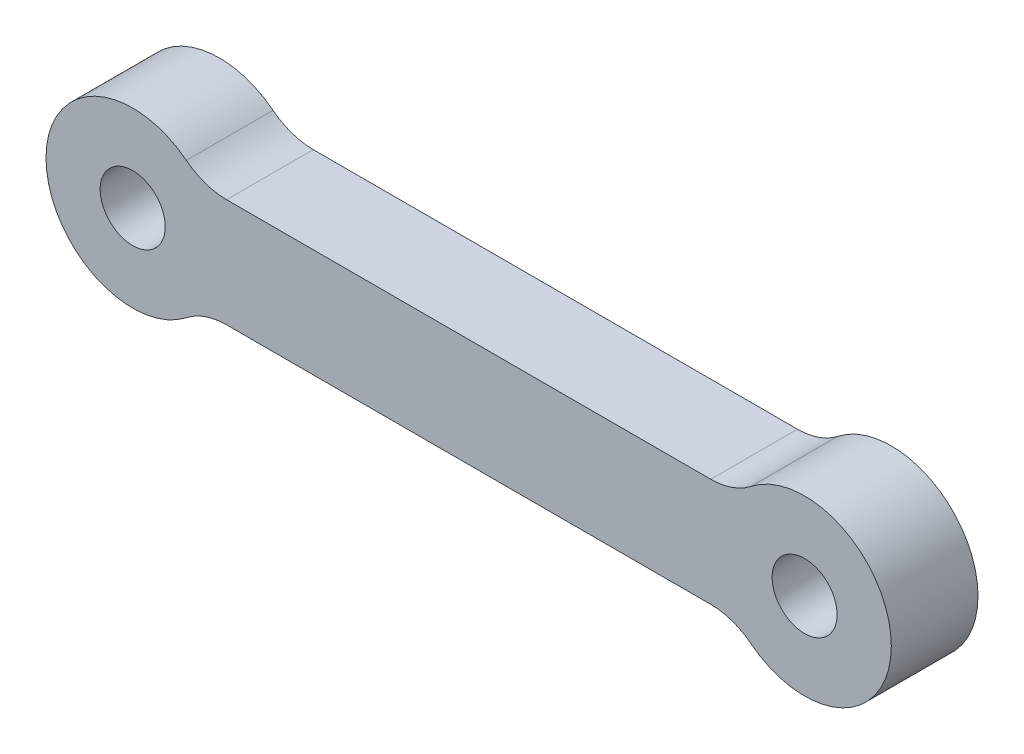
SolidWorks part; units mm, degrees
ref_plane "Front Plane" through (0, 0, 0) normal (0, 0, 1) x (1, 0, 0)
ref_plane "Top Plane" through (0, 0, 0) normal (0, 1, 0) x (1, 0, 0)
ref_plane "Right Plane" through (0, 0, 0) normal (1, 0, 0) x (0, 0, -1)
sketch "Sketch1" plane through (0, 0, 0) normal (0, 0, 1) x (1, 0, 0)
  line L0 (-15.5, 0) -> (15.5, 0) construction
  line L1 (0, 0) -> (0, 2.8532) construction
  line L3 (-11.1699, -2.5) -> (11.1699, -2.5)
  line L5 (-11.1699, 2.5) -> (11.1699, 2.5)
  line L7 (-12.3775, -2.5) -> (12.3775, 2.5) construction
  line L8 (-12.3775, 2.5) -> (12.3775, -2.5) construction
  circle A0 centre (-15.5, 0) radius 1.5
  arc A1 (-13.0256, 3.1429) -> (-13.0256, -3.1429) centre (-15.5, 0) ccw
  arc A2 (13.0256, 3.1429) -> (13.0256, -3.1429) centre (15.5, 0) cw
  circle A3 centre (15.5, 0) radius 1.5
  arc A4 (11.1699, 2.5) -> (13.0256, 3.1429) centre (11.1699, 5.5) ccw
  arc A5 (11.1699, -2.5) -> (13.0256, -3.1429) centre (11.1699, -5.5) cw
  arc A6 (-11.1699, -2.5) -> (-13.0256, -3.1429) centre (-11.1699, -5.5) ccw
  arc A7 (-13.0256, 3.1429) -> (-11.1699, 2.5) centre (-11.1699, 5.5) ccw
  point P4 (0, 0)
  dimension "D2" = 8
  dimension "D3" = 3
  dimension "D5" = 3
  dimension "D1" = 31
  dimension "D4" = 5
extrude "Boss-Extrude1" add sketch "Sketch1" along normal blind 4
